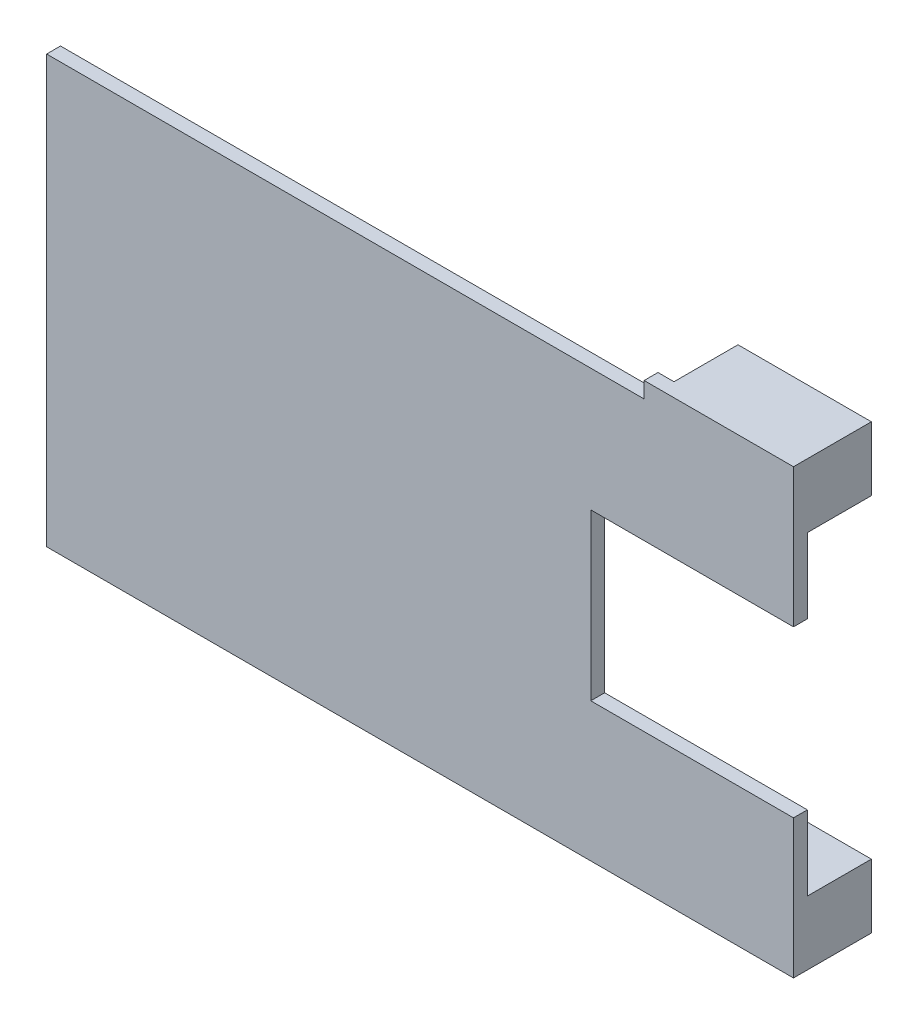
SolidWorks part; units mm, degrees
ref_plane "Přední rovina" through (0, 0, 0) normal (0, 0, 1) x (1, 0, 0)
ref_plane "Horní rovina" through (0, 0, 0) normal (0, 1, 0) x (1, 0, 0)
ref_plane "Pravá rovina" through (0, 0, 0) normal (1, 0, 0) x (0, 0, -1)
sketch "Sketch2" plane through (0, 0, 0) normal (0, 0, 1) x (1, 0, 0)
  line L0 (70, 40) -> (70, 0)
  line L1 (0, 0) -> (70, 0)
  line L2 (0, 0) -> (0, 40)
  line L3 (0, 40) -> (70, 40)
  dimension "D1" = 40
  dimension "D2" = 70
extrude "Boss-Extrude1" add sketch "Sketch2" along normal blind 1.3
sketch "Sketch4" plane through (0, 40, 0) normal (0, 1, 0) x (1, 0, 0)
  line L0 (0, -1.3) -> (70, -1.3) construction
  line L5 (70, 0) -> (56, 0)
  line L6 (70, 0) -> (70, -1.3)
  line L7 (70, -1.3) -> (56, -1.3)
  line L8 (56, 0) -> (56, -1.3)
  dimension "D1" = 14
extrude "Boss-Extrude3" add sketch "Sketch4" along normal blind 1.5
sketch "Sketch6" plane through (0, 0, 1.3) normal (0, 0, 1) x (1, 0, 0)
  line L0 (70, 28.5) -> (51, 28.5)
  line L1 (70, 41.5) -> (70, 0) construction
  line L2 (51, 28.5) -> (51, 13)
  line L3 (51, 13) -> (70, 13)
  line L4 (70, 13) -> (70, 28.5)
  line L5 (56, 41.5) -> (70, 41.5) construction
  line L6 (0, 0) -> (70, 0) construction
  dimension "D1" = 13
  dimension "D2" = 13
  dimension "D3" = 19
sketch "Sketch8" plane through (0, 0, 0) normal (0, 0, -1) x (-1, 0, 0)
  line L2 (-70, 41.5) -> (-57.5, 41.5)
  line L3 (-70, 41.5) -> (-70, 35.5)
  line L4 (-70, 35.5) -> (-57.5, 35.5)
  line L5 (-57.5, 41.5) -> (-57.5, 35.5)
  line L6 (-70, 0) -> (-57.5, 0)
  line L7 (-70, 0) -> (-70, 6)
  line L8 (-70, 6) -> (-57.5, 6)
  line L9 (-57.5, 0) -> (-57.5, 6)
  dimension "D1" = 12.5
  dimension "D2" = 6
  dimension "D3" = 12.5
  dimension "D4" = 6
extrude "Boss-Extrude4" add sketch "Sketch8" along normal blind 6
sketch "Sketch9" plane through (0, 0, -6) normal (0, 0, -1) x (-1, 0, 0)
  line L0 (-57.5, 35.5) -> (-57.5, 41.5) construction
  line L1 (-66.5, 39.65) -> (-65.5, 39.65)
  line L2 (-66.5, 39.65) -> (-66.5, 37.35)
  line L3 (-66.5, 37.35) -> (-65.5, 37.35)
  line L4 (-65.5, 39.65) -> (-65.5, 37.35)
  line L5 (-66.5, 4.15) -> (-65.5, 4.15)
  line L6 (-66.5, 4.15) -> (-66.5, 1.85)
  line L7 (-66.5, 1.85) -> (-65.5, 1.85)
  line L8 (-65.5, 4.15) -> (-65.5, 1.85)
  line L9 (-57.5, 0) -> (-57.5, 6) construction
  line L10 (-70, 6) -> (-70, 0) construction
  line L11 (-70, 41.5) -> (-70, 35.5) construction
  point P12 (-70, 3)
  point P15 (-66.5, 3)
  point P18 (-70, 38.5)
  point P19 (-66.5, 38.5)
  dimension "D1" = 8
  dimension "D2" = 8
  dimension "D3" = 2.3
  dimension "D4" = 1
  dimension "D5" = 2.3
  dimension "D6" = 1
  dimension "D7" = 3.5
  dimension "D8" = 3.5
extrude "Boss-Extrude5" add sketch "Sketch9" along normal blind 0.8
extrude "Cut-Extrude1" cut sketch "Sketch6" against normal up to surface (1.3 mm away) up to face at (48.2, 24.6, 0)
